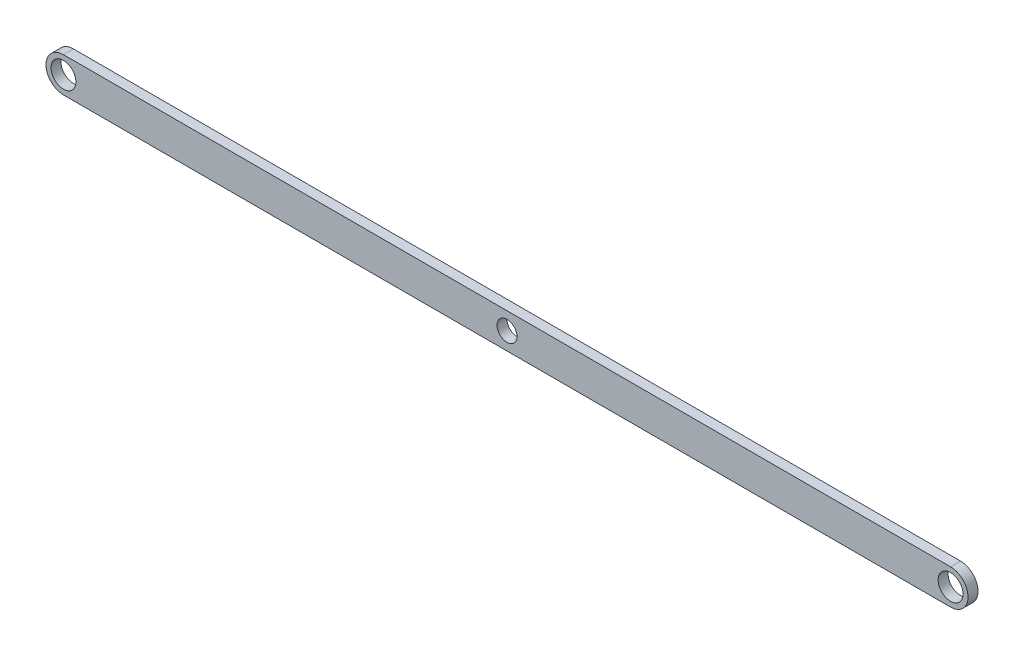
SolidWorks part; units mm, degrees
ref_plane "정면" through (0, 0, 0) normal (0, 0, 1) x (1, 0, 0)
ref_plane "윗면" through (0, 0, 0) normal (0, 1, 0) x (1, 0, 0)
ref_plane "우측면" through (0, 0, 0) normal (1, 0, 0) x (0, 0, -1)
sketch "스케치1" plane through (0, 0, 0) normal (0, 0, 1) x (1, 0, 0)
  line L0 (-92.2616, 23.2291) -> (85.7384, 23.2291)
  line L1 (-92.2616, 19.7291) -> (-92.2616, -16.1909) construction
  line L2 (85.7384, 16.2291) -> (-92.2616, 16.2291)
  line L3 (-3.2616, 23.2291) -> (-3.2616, 16.2291) construction
  line L7 (85.7384, 19.7291) -> (85.7384, -16.1909) construction
  line L11 (-95.7616, 19.7291) -> (89.2384, 19.7291) construction
  circle A0 centre (-92.2616, 19.7291) radius 2.5
  arc A1 (-92.2616, 23.2291) -> (-92.2616, 16.2291) centre (-92.2616, 19.7291) ccw
  arc A2 (85.7384, 23.2291) -> (85.7384, 16.2291) centre (85.7384, 19.7291) cw
  circle A3 centre (85.7384, 19.7291) radius 2.5
  circle A4 centre (-3.2616, 19.7291) radius 2
  point P4 (-88.6016, 16.2291)
  point P5 (89.2384, 16.2291)
  point P16 (-95.7616, 19.7291)
  point P19 (89.2384, 19.7291)
  point P25 (-92.2616, 19.7291)
  dimension "D4" = 35.92
  dimension "D1" = 4
  dimension "D3" = 3.5
  dimension "D2" = 185
  dimension "D5" = 35.92
  dimension "D6" = 3.5
  dimension "D7" = 92.5
  dimension "D8" = 3.5
extrude "보스-돌출1" add sketch "스케치1" along normal blind 2
